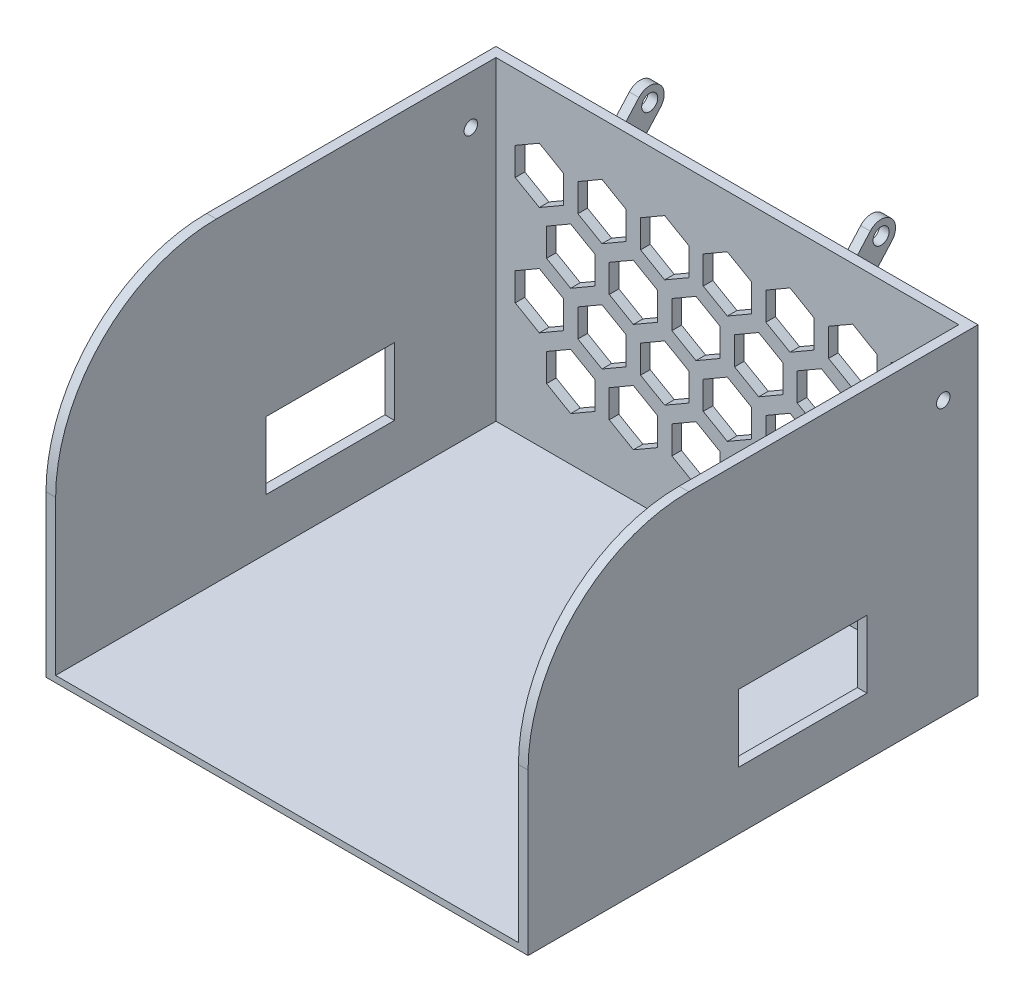
SolidWorks part; units mm, degrees
material "PLA"
ref_plane "Front Plane" through (0, 0, 0) normal (0, 0, 1) x (1, 0, 0)
ref_plane "Top Plane" through (0, 0, 0) normal (0, 1, 0) x (1, 0, 0)
ref_plane "Right Plane" through (0, 0, 0) normal (1, 0, 0) x (0, 0, -1)
sketch "Sketch1" plane through (0, 0, 0) normal (1, 0, 0) x (0, 0, -1)
  line L0 (0, 0) -> (-140, 0)
  line L1 (-140, 0) -> (-140, 50)
  line L2 (-90, 100) -> (0, 100)
  line L3 (0, 100) -> (0, 0)
  arc A0 (-140, 50) -> (-90, 100) centre (-90, 50) cw
  dimension "D1" = 140
  dimension "D2" = 100
  dimension "D3" = 50
extrude "Boss-Extrude1" add sketch "Sketch1" along normal blind 150 contours A0 L2 L3 L0 L1
sketch "Sketch2" plane through (0, 100, 0) normal (0, 1, 0) x (1, 0, 0)
  line L0 (150, 0) -> (0, 0) construction
  line L1 (3, -3) -> (147, -3)
  line L2 (3, -3) -> (3, -145)
  line L3 (3, -145) -> (147, -145)
  line L4 (147, -3) -> (147, -145)
  line L5 (150, -90) -> (150, 0) construction
  line L6 (0, -90) -> (0, 0) construction
  line L8 (150, -140) -> (0, -140) construction
  dimension "D1" = 3
  dimension "D2" = 3
  dimension "D3" = 3
  dimension "D4" = 5
extrude "Cut-Extrude1" cut sketch "Sketch2" against normal offset from surface (98 mm away) 2 up to face at (75, 0, 70)
ref_plane "Plane1" through (75, 0, 0) normal (1, 0, 0) x (0, 0, -1)
ref_plane "Plane2" through (111, 0, 0) normal (1, 0, 0) x (0, 0, -1)
ref_plane "Plane3" through (39, 0, 0) normal (1, 0, 0) x (0, 0, -1)
sketch "Sketch3" plane through (111, 0, 0) normal (1, 0, 0) x (0, 0, -1)
  line L0 (0, 100) -> (0, 86.4837)
  line L1 (0, 86.4837) -> (10.7098, 98.4837)
  line L2 (3.9952, 104.4764) -> (0, 100)
  arc A0 (10.7098, 98.4837) -> (3.9952, 104.4764) centre (7.3525, 101.4801) ccw
  circle A1 centre (7.3525, 101.4801) radius 2.5
  dimension "D1" = 2
  dimension "D2" = 5
  dimension "D3" = 6
  dimension "D4" = 12
extrude "Boss-Extrude2" add sketch "Sketch3" along normal mid plane 3
mirror "Mirror1" about plane through (75, 0, 0) normal (1, 0, 0) of "Boss-Extrude2"
sketch "Sketch4" plane through (150, 0, 0) normal (1, 0, 0) x (0, 0, -1)
  line L0 (-10.8107, 85.0634) -> (-67.3793, 28.4949) construction
  line L1 (-74.5612, 38.9949) -> (-74.5612, 17.9949)
  line L2 (-74.5612, 17.9949) -> (-34.5612, 17.9949)
  line L3 (0, 0) -> (-140, 0) construction
  line L4 (-34.5612, 17.9949) -> (-34.5612, 38.9949)
  line L5 (-34.5612, 38.9949) -> (-74.5612, 38.9949)
  circle A0 centre (-67.3793, 28.4949) radius 2.5
  circle A1 centre (-10.8107, 85.0634) radius 2.1
  point P8 (-74.5612, 28.4949)
  dimension "D4" = 4.2
  dimension "D5" = 5
  dimension "D1" = 80
  dimension "D2" = 45
  dimension "D3" = 40
  dimension "D6" = 21
extrude "Cut-Extrude2" cut sketch "Sketch4" against normal up to next
mirror "Mirror2" about plane through (75, 0, 0) normal (1, 0, 0) of "Cut-Extrude2"
sketch "Sketch5" plane through (0, 0, 0) normal (0, 0, -1) x (-1, 0, 0)
  line L0 (-150, 75) -> (0, 75) construction
  line L1 (-150, 100) -> (-150, 0) construction
  line L2 (0, 100) -> (0, 0) construction
  line L3 (-75, 100) -> (-75, 0) construction
  line L4 (-109.5, 100) -> (-40.5, 100) construction
  line L5 (-75, 91.3518) -> (-75, -91.3518) construction
  line L6 (-114, 83.6603) -> (-121.5, 79.3301)
  line L7 (-133.5, 83.6603) -> (-141, 79.3301)
  line L8 (-141, 79.3301) -> (-141, 70.6699)
  line L9 (-141, 70.6699) -> (-133.5, 66.3397)
  line L10 (-133.5, 66.3397) -> (-126, 70.6699)
  line L11 (-126, 70.6699) -> (-126, 79.3301)
  line L12 (-126, 79.3301) -> (-133.5, 83.6603)
  line L13 (-121.5, 79.3301) -> (-121.5, 70.6699)
  line L14 (-121.5, 70.6699) -> (-114, 66.3397)
  line L15 (-114, 66.3397) -> (-106.5, 70.6699)
  line L16 (-106.5, 70.6699) -> (-106.5, 79.3301)
  line L17 (-106.5, 79.3301) -> (-114, 83.6603)
  line L18 (-94.5, 83.6603) -> (-102, 79.3301)
  line L19 (-102, 79.3301) -> (-102, 70.6699)
  line L20 (-102, 70.6699) -> (-94.5, 66.3397)
  line L21 (-94.5, 66.3397) -> (-87, 70.6699)
  line L22 (-87, 70.6699) -> (-87, 79.3301)
  line L23 (-87, 79.3301) -> (-94.5, 83.6603)
  line L24 (-75, 83.6603) -> (-82.5, 79.3301)
  line L25 (-82.5, 79.3301) -> (-82.5, 70.6699)
  line L26 (-82.5, 70.6699) -> (-75, 66.3397)
  line L27 (-75, 66.3397) -> (-67.5, 70.6699)
  line L28 (-67.5, 70.6699) -> (-67.5, 79.3301)
  line L29 (-67.5, 79.3301) -> (-75, 83.6603)
  line L30 (-55.5, 83.6603) -> (-63, 79.3301)
  line L31 (-63, 79.3301) -> (-63, 70.6699)
  line L32 (-63, 70.6699) -> (-55.5, 66.3397)
  line L33 (-55.5, 66.3397) -> (-48, 70.6699)
  line L34 (-48, 70.6699) -> (-48, 79.3301)
  line L35 (-48, 79.3301) -> (-55.5, 83.6603)
  line L36 (-36, 83.6603) -> (-43.5, 79.3301)
  line L37 (-43.5, 79.3301) -> (-43.5, 70.6699)
  line L38 (-43.5, 70.6699) -> (-36, 66.3397)
  line L39 (-36, 66.3397) -> (-28.5, 70.6699)
  line L40 (-28.5, 70.6699) -> (-28.5, 79.3301)
  line L41 (-28.5, 79.3301) -> (-36, 83.6603)
  line L42 (-16.5, 83.6603) -> (-24, 79.3301)
  line L43 (-24, 79.3301) -> (-24, 70.6699)
  line L44 (-24, 70.6699) -> (-16.5, 66.3397)
  line L45 (-16.5, 66.3397) -> (-9, 70.6699)
  line L46 (-9, 70.6699) -> (-9, 79.3301)
  line L47 (-9, 79.3301) -> (-16.5, 83.6603)
  line L48 (-150, 58.1125) -> (0, 58.1125) construction
  line L49 (-123.75, 58.1125) -> (-123.75, 75) construction
  line L50 (-123.75, 66.7728) -> (-131.25, 62.4426)
  line L51 (-131.25, 62.4426) -> (-131.25, 53.7824)
  line L52 (-131.25, 53.7824) -> (-123.75, 49.4523)
  line L53 (-123.75, 49.4523) -> (-116.25, 53.7824)
  line L54 (-116.25, 53.7824) -> (-116.25, 62.4426)
  line L55 (-116.25, 62.4426) -> (-123.75, 66.7728)
  line L56 (-37.5, 100) -> (0, 100) construction
  line L57 (-104.25, 66.7728) -> (-111.75, 62.4426)
  line L58 (-111.75, 62.4426) -> (-111.75, 53.7824)
  line L59 (-111.75, 53.7824) -> (-104.25, 49.4523)
  line L60 (-104.25, 49.4523) -> (-96.75, 53.7824)
  line L61 (-96.75, 53.7824) -> (-96.75, 62.4426)
  line L62 (-96.75, 62.4426) -> (-104.25, 66.7728)
  line L63 (-84.75, 66.7728) -> (-92.25, 62.4426)
  line L64 (-92.25, 62.4426) -> (-92.25, 53.7824)
  line L65 (-92.25, 53.7824) -> (-84.75, 49.4523)
  line L66 (-84.75, 49.4523) -> (-77.25, 53.7824)
  line L67 (-77.25, 53.7824) -> (-77.25, 62.4426)
  line L68 (-77.25, 62.4426) -> (-84.75, 66.7728)
  line L69 (-65.25, 66.7728) -> (-72.75, 62.4426)
  line L70 (-72.75, 62.4426) -> (-72.75, 53.7824)
  line L71 (-72.75, 53.7824) -> (-65.25, 49.4523)
  line L72 (-65.25, 49.4523) -> (-57.75, 53.7824)
  line L73 (-57.75, 53.7824) -> (-57.75, 62.4426)
  line L74 (-57.75, 62.4426) -> (-65.25, 66.7728)
  line L75 (-45.75, 66.7728) -> (-53.25, 62.4426)
  line L76 (-53.25, 62.4426) -> (-53.25, 53.7824)
  line L77 (-53.25, 53.7824) -> (-45.75, 49.4523)
  line L78 (-45.75, 49.4523) -> (-38.25, 53.7824)
  line L79 (-38.25, 53.7824) -> (-38.25, 62.4426)
  line L80 (-38.25, 62.4426) -> (-45.75, 66.7728)
  line L81 (-26.25, 66.7728) -> (-33.75, 62.4426)
  line L82 (-33.75, 62.4426) -> (-33.75, 53.7824)
  line L83 (-33.75, 53.7824) -> (-26.25, 49.4523)
  line L84 (-26.25, 49.4523) -> (-18.75, 53.7824)
  line L85 (-18.75, 53.7824) -> (-18.75, 62.4426)
  line L86 (-18.75, 62.4426) -> (-26.25, 66.7728)
  line L87 (-9, 36.8949) -> (-16.5, 32.5648)
  line L88 (-9, 45.5551) -> (-9, 36.8949)
  line L89 (-16.5, 49.8853) -> (-9, 45.5551)
  line L90 (-24, 45.5551) -> (-16.5, 49.8853)
  line L91 (-24, 36.8949) -> (-24, 45.5551)
  line L92 (-16.5, 32.5648) -> (-24, 36.8949)
  line L93 (-28.5, 36.8949) -> (-36, 32.5648)
  line L94 (-28.5, 45.5551) -> (-28.5, 36.8949)
  line L95 (-36, 49.8853) -> (-28.5, 45.5551)
  line L96 (-43.5, 45.5551) -> (-36, 49.8853)
  line L97 (-43.5, 36.8949) -> (-43.5, 45.5551)
  line L98 (-36, 32.5648) -> (-43.5, 36.8949)
  line L99 (-48, 36.8949) -> (-55.5, 32.5648)
  line L100 (-48, 45.5551) -> (-48, 36.8949)
  line L101 (-55.5, 49.8853) -> (-48, 45.5551)
  line L102 (-63, 45.5551) -> (-55.5, 49.8853)
  line L103 (-63, 36.8949) -> (-63, 45.5551)
  line L104 (-55.5, 32.5648) -> (-63, 36.8949)
  line L105 (-67.5, 36.8949) -> (-75, 32.5648)
  line L106 (-67.5, 45.5551) -> (-67.5, 36.8949)
  line L107 (-75, 49.8853) -> (-67.5, 45.5551)
  line L108 (-82.5, 45.5551) -> (-75, 49.8853)
  line L109 (-82.5, 36.8949) -> (-82.5, 45.5551)
  line L110 (-75, 32.5648) -> (-82.5, 36.8949)
  line L111 (-87, 36.8949) -> (-94.5, 32.5648)
  line L112 (-87, 45.5551) -> (-87, 36.8949)
  line L113 (-94.5, 49.8853) -> (-87, 45.5551)
  line L114 (-102, 45.5551) -> (-94.5, 49.8853)
  line L115 (-102, 36.8949) -> (-102, 45.5551)
  line L116 (-94.5, 32.5648) -> (-102, 36.8949)
  line L117 (-106.5, 36.8949) -> (-114, 32.5648)
  line L118 (-106.5, 45.5551) -> (-106.5, 36.8949)
  line L119 (-114, 49.8853) -> (-106.5, 45.5551)
  line L120 (-121.5, 45.5551) -> (-114, 49.8853)
  line L121 (-121.5, 36.8949) -> (-121.5, 45.5551)
  line L122 (-114, 32.5648) -> (-121.5, 36.8949)
  line L123 (-126, 36.8949) -> (-133.5, 32.5648)
  line L124 (-126, 45.5551) -> (-126, 36.8949)
  line L125 (-133.5, 49.8853) -> (-126, 45.5551)
  line L126 (-141, 45.5551) -> (-133.5, 49.8853)
  line L127 (-141, 36.8949) -> (-141, 45.5551)
  line L128 (-133.5, 32.5648) -> (-141, 36.8949)
  line L129 (-141, 41.225) -> (-9, 41.225) construction
  line L130 (-18.75, 20.0074) -> (-26.25, 15.6773)
  line L131 (-18.75, 28.6676) -> (-18.75, 20.0074)
  line L132 (-26.25, 32.9978) -> (-18.75, 28.6676)
  line L133 (-33.75, 28.6676) -> (-26.25, 32.9978)
  line L134 (-33.75, 20.0074) -> (-33.75, 28.6676)
  line L135 (-26.25, 15.6773) -> (-33.75, 20.0074)
  line L136 (-38.25, 20.0074) -> (-45.75, 15.6773)
  line L137 (-38.25, 28.6676) -> (-38.25, 20.0074)
  line L138 (-45.75, 32.9978) -> (-38.25, 28.6676)
  line L139 (-53.25, 28.6676) -> (-45.75, 32.9978)
  line L140 (-53.25, 20.0074) -> (-53.25, 28.6676)
  line L141 (-45.75, 15.6773) -> (-53.25, 20.0074)
  line L142 (-57.75, 20.0074) -> (-65.25, 15.6773)
  line L143 (-57.75, 28.6676) -> (-57.75, 20.0074)
  line L144 (-65.25, 32.9978) -> (-57.75, 28.6676)
  line L145 (-72.75, 28.6676) -> (-65.25, 32.9978)
  line L146 (-72.75, 20.0074) -> (-72.75, 28.6676)
  line L147 (-65.25, 15.6773) -> (-72.75, 20.0074)
  line L148 (-77.25, 20.0074) -> (-84.75, 15.6773)
  line L149 (-77.25, 28.6676) -> (-77.25, 20.0074)
  line L150 (-84.75, 32.9978) -> (-77.25, 28.6676)
  line L151 (-92.25, 28.6676) -> (-84.75, 32.9978)
  line L152 (-92.25, 20.0074) -> (-92.25, 28.6676)
  line L153 (-84.75, 15.6773) -> (-92.25, 20.0074)
  line L154 (-96.75, 20.0074) -> (-104.25, 15.6773)
  line L155 (-96.75, 28.6676) -> (-96.75, 20.0074)
  line L156 (-104.25, 32.9978) -> (-96.75, 28.6676)
  line L157 (-111.75, 28.6676) -> (-104.25, 32.9978)
  line L158 (-111.75, 20.0074) -> (-111.75, 28.6676)
  line L159 (-104.25, 15.6773) -> (-111.75, 20.0074)
  line L160 (-116.25, 20.0074) -> (-123.75, 15.6773)
  line L161 (-116.25, 28.6676) -> (-116.25, 20.0074)
  line L162 (-123.75, 32.9978) -> (-116.25, 28.6676)
  line L163 (-131.25, 28.6676) -> (-123.75, 32.9978)
  line L164 (-131.25, 20.0074) -> (-131.25, 28.6676)
  line L165 (-123.75, 15.6773) -> (-131.25, 20.0074)
  circle A0 centre (-133.5, 75) radius 7.5 construction
  circle A1 centre (-123.75, 58.1125) radius 7.5 construction
  point P71 (-120, 64.6077)
  point P72 (-117.75, 68.5048)
  dimension "D2" = 15
  dimension "D3" = 9
  dimension "D4" = 9
  dimension "D5" = 25
  dimension "D6" = 4.5
  dimension "D8" = 18.75
  dimension "D1" = 7
  dimension "D7" = 6
extrude "Cut-Extrude3" cut sketch "Sketch5" against normal blind 10
equation "\"forward_length\"= 130"
equation "\"height\"= 100"
equation "\"eslabon_AB\"=80"
